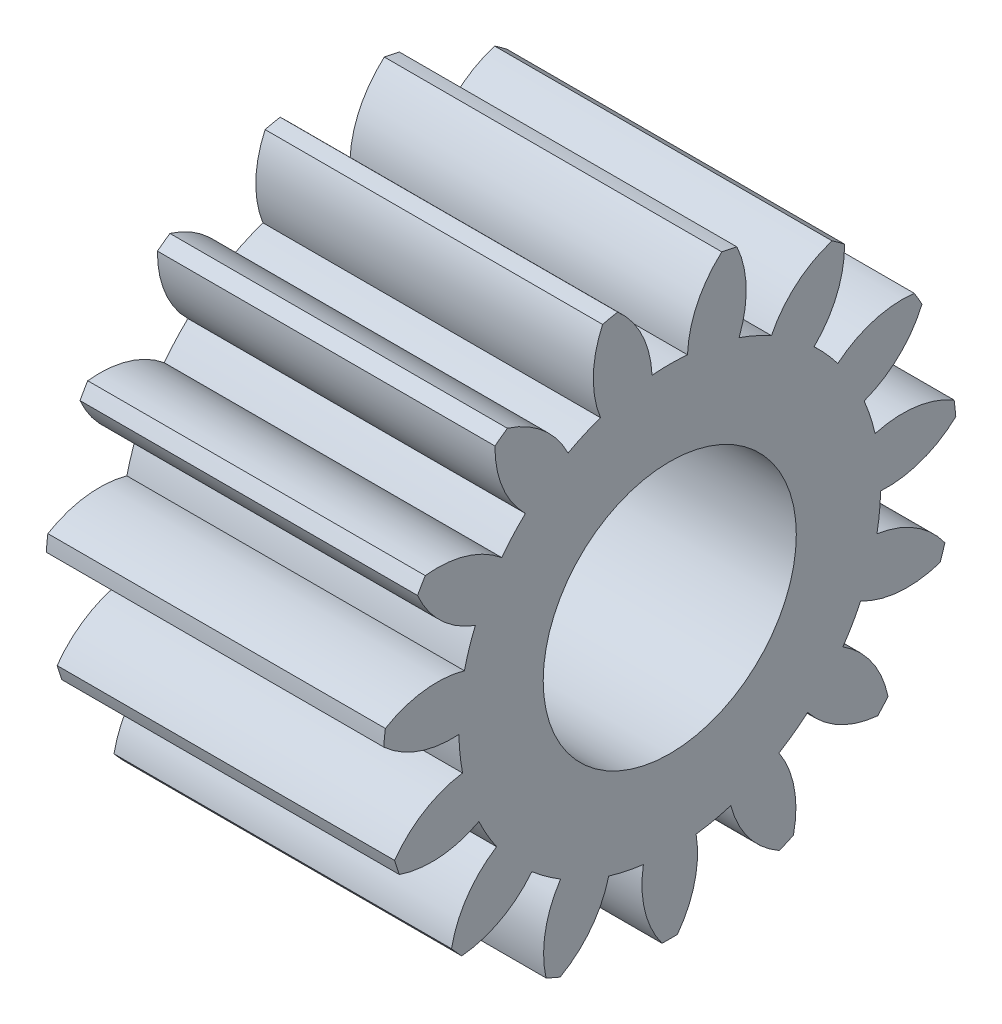
SolidWorks part; units mm, degrees
ref_plane "Plane1" through (0, 0, 0) normal (0, 0, 1) x (1, 0, 0)
ref_plane "Plane2" through (0, 0, 0) normal (0, 1, 0) x (1, 0, 0)
ref_plane "Plane3" through (0, 0, 0) normal (1, 0, 0) x (0, 0, -1)
sketch "HoldingSke" plane through (0, 0, 0) normal (0, 1, 0) x (1, 0, 0)
  line L0 (0, 0) -> (0.483, -0.1294)
  line L1 (-15, 0) -> (100, 0) construction
  line L2 (0, 0) -> (-2.1039, 2.3779)
  line L3 (0, 0) -> (-11.863, 4.5341)
  line L4 (0, 0) -> (8.3417, 2.2352)
  line L5 (0, 0) -> (-46.8476, -17.4728)
  line L6 (0, 0) -> (-16.5793, -11.1861)
  line L7 (-2.1039, 2.3779) -> (8.6586, 51.2059)
  line L8 (-76.2, 54.61) -> (-73.9, 54.61)
  line L9 (-71.009, 38.7566) -> (-53.1078, 45.2721)
  line L10 (-76.2, 71.12) -> (104.1128, 71.12)
  line L11 (0, 0) -> (-20, 0)
  line L12 (-76.2, 101.6) -> (-76.133, 101.6)
  line L13 (24.9733, 27.94) -> (52.9518, 28.4284)
  line L14 (24.9733, 27.94) -> (24.9743, 27.94)
  line L15 (24.9733, 27.94) -> (100.4006, 29.5858)
  line L16 (-63.627, -2) -> (-12.827, -2)
  circle A0 centre (0, 0) radius 7.5
  circle A1 centre (0, 0) radius 12.499
  circle A2 centre (0, 0) radius 37.5
  circle A3 centre (0, 0) radius 7.5
  dimension "MHD" = 24.998
  dimension "Hub_dia" = 75
  dimension "Bore" = 15
  dimension "MBD" = 15
  dimension "Num_teeth" = 15
  dimension "Pitch" = 0.5
  dimension "Overall_len" = 50
  dimension "Show_teeth" = 15
  dimension "Thickness" = 20
  dimension "OAL" = 50.0001
  dimension "T_dim" = 2.3
  dimension "Ap" = 20
  dimension "H" = 19.05
  dimension "Pitch_radius" = 180.3128
  dimension "Width" = 20
  dimension "Backlash" = 0.067
  dimension "Addendum_fac" = 1
  dimension "Dedendum_fac" = 1.25
  dimension "Clearance_fac" = 0.25
  dimension "Dedendum_add" = 0.001
  dimension "Module" = 2
sketch "BasProSke" plane through (0, 0, 0) normal (0, 1, 0) x (1, 0, 0)
  line L0 (-10, 0) -> (60, 0) construction
  line L1 (0, 0) -> (0, 17)
  line L2 (0, 0) -> (20, 0)
  line L3 (20, 0) -> (20, 17)
  line L4 (20, 17) -> (0, 17)
  dimension "Thickness" = 20
  dimension "Diameter" = 34
revolve "Base-Revolve" add sketch "BasProSke" angle 360 about L0
sketch "TooCutSke" plane through (0, 0, 0) normal (1, 0, 0) x (0, 0, -1)
  line L1 (0, 0) -> (0, 107) construction
  line L2 (0, 0) -> (-1.6851, 14.905) construction
  line L3 (0, 0) -> (-6.2081, 29.2069) construction
  line L4 (-1.6851, 14.905) -> (-3.1041, 14.6034) construction
  arc A0 (1.0501, 12.4548) -> (-1.0501, 12.4548) centre (0, 0) ccw
  arc A1 (3.1109, 16.7388) -> (-3.1109, 16.7388) centre (0, 0) ccw
  circle A2 centre (0, 0) radius 15 construction
  circle A3 centre (0, 0) radius 14.0954 construction
  arc A4 (-1.0501, 12.4548) -> (-3.1109, 16.7388) centre (-7.045, 12.2085) ccw
  arc A5 (3.1109, 16.7388) -> (1.0501, 12.4548) centre (7.045, 12.2085) ccw
  dimension "Root_dia" = 24.998
  dimension "Overcut_dia" = 34.0508
  dimension "Pitch_dia" = 30
  dimension "Base_dia" = 28.1908
  dimension "Flank_rad" = 6
  dimension "Half_ang" = 12
  dimension "Half_CT" = 1.4507
extrude "ToothCut" cut sketch "TooCutSke" along normal through all
fillet "Breaks" [suppressed] radius 0.04
fillet "RootFillets" [suppressed] radius 0.501
pattern_circular "TeethCuts" count 15 every 24 about axis through (-10, 0, 0) along (1, 0, 0) of "ToothCut", "RootFillets", "Breaks"
sketch "HubNeaOneSke" plane through (0, 0, 0) normal (-1, 0, 0) x (0, 0, 1)
  circle A0 centre (0, 0) radius 12.499
  dimension "Diameter" = 24.998
extrude "HubNearOne" [suppressed] add sketch "HubNeaOneSke" along normal blind 30.0001
sketch "HubNeaBotSke" plane through (0, 0, 0) normal (-1, 0, 0) x (0, 0, 1)
  circle A0 centre (0, 0) radius 12.499
  dimension "Diameter" = 24.998
extrude "HubNearBoth" [suppressed] add sketch "HubNeaBotSke" along normal blind 15
ref_plane "FarPln" through (20, 0, 0) normal (1, 0, 0) x (0, 0, -1)
sketch "HubFarSke" plane through (20, 0, 0) normal (1, 0, 0) x (0, 0, -1)
  circle A0 centre (0, 0) radius 12.499
  dimension "Diameter" = 24.998
extrude "HubFar" [suppressed] add sketch "HubFarSke" along normal blind 15
sketch "BorSke" plane through (0, 0, 0) normal (1, 0, 0) x (0, 0, -1)
  circle A0 centre (0, 0) radius 7.5
  dimension "Diameter" = 15
extrude "Bore" cut sketch "BorSke" along normal mid plane 100.0001
sketch "KeySke" plane through (0, 0, 0) normal (1, 0, 0) x (0, 0, -1)
  line L0 (-2.5, 0) -> (-2.5, 9.8)
  line L1 (-2.5, 9.8) -> (2.5, 9.8)
  line L2 (2.5, 9.8) -> (2.5, 0)
  line L3 (0, 0) -> (0, 34) construction
  line L4 (-2.5, 0) -> (2.5, 0)
  dimension "Offset" = 9.8
  dimension "Width" = 5
extrude "Keyway" [suppressed] cut sketch "KeySke" along normal mid plane 100.0001
pattern_circular "Keyway2" [suppressed] count 2 every 90 about axis through (-10, 0, 0) along (1, 0, 0)
equation "' \"Module@HoldingSke\" = 6.35"
equation "' \"Num_teeth@HoldingSke\" = 12"
equation "' \"Ap@HoldingSke\" =  20"
equation "' \"Ap@HoldingSke\" = 20"
equation "' \"Width@HoldingSke\" = 0.5 * 25.4"
equation "' \"Hub_dia@HoldingSke\"= 1 * 25.4"
equation "' \"Hub_dia@HoldingSke\" = 1 * 25.4"
equation "' \"Overall_len@HoldingSke\" = 1.0 * 25.4"
equation "' \"Bore@HoldingSke\" = 0.75 * 25.4"
equation "' \"T_dim@HoldingSke\" = 0.1 * 25.4"
equation "' \"Width@KeySke\" = 0.25 * 25.4"
equation "' \"Show_teeth@HoldingSke\" = 13"
equation "' \"Backlash@HoldingSke\" = 0.009 * 25.4"
equation "' \"Addendum_fac@HoldingSke\" = 1.0"
equation "' \"Dedendum_fac@HoldingSke\" = 1.25"
equation "' \"Dedendum_add@HoldingSke\" = 0.00005 * 25.4"
equation "' \"Clearance_fac@HoldingSke\" = 0.25"
equation "\"Pitch@HoldingSke\" = 1 / \"Module@HoldingSke\""
equation "\"Overcut_dia@TooCutSke\" = (\"Num_teeth@HoldingSke\" + 2 * \"Addendum_fac@HoldingSke\") / \"Pitch@HoldingSke\" + 0.002 * 25.4"
equation "\"Pitch_dia@TooCutSke\" = \"Num_teeth@HoldingSke\" / \"Pitch@HoldingSke\""
equation "\"Base_dia@TooCutSke\" = \"Num_teeth@HoldingSke\" / \"Pitch@HoldingSke\" * cos((\"Ap@HoldingSke\"  * 3.14159265 / 180))"
equation "\"Root_dia@TooCutSke\" = (\"Num_teeth@HoldingSke\" + 2) / \"Pitch@HoldingSke\" - 2 * (\"Addendum_fac@HoldingSke\" + \"Dedendum_fac@HoldingSke\") / \"Pitch@HoldingSke\" - \"Dedendum_add@HoldingSke\" * 2"
equation "\"Half_ang@TooCutSke\" = 180 / \"Num_teeth@HoldingSke\""
equation "\"Half_CT@TooCutSke\" = \"Num_teeth@HoldingSke\" / \"Pitch@HoldingSke\" * sin((3.14159265 / 2 / \"Num_teeth@HoldingSke\")) / 2 - 7 * \"Backlash@HoldingSke\" / 4"
equation "\"Flank_rad@TooCutSke\" = \"Num_teeth@HoldingSke\" / \"Pitch@HoldingSke\" / 5"
equation "\"Radius@RootFillets\" = \"Clearance_fac@HoldingSke\" / \"Pitch@HoldingSke\" + \"Dedendum_add@HoldingSke\""
equation "\"Break_rad@Breaks\" = 0.02 / \"Pitch@HoldingSke\""
equation "\"Thickness@HoldingSke\" = \"Width@HoldingSke\""
equation "\"OAL@HoldingSke\" = \"Thickness@HoldingSke\""
equation "\"MHD@HoldingSke\" = (\"Num_teeth@HoldingSke\" + 2) / \"Pitch@HoldingSke\" - 2 * (\"Addendum_fac@HoldingSke\" + \"Dedendum_fac@HoldingSke\")  / \"Pitch@HoldingSke\" - \"Dedendum_add@HoldingSke\" * 2"
equation "\"MBD@HoldingSke\" = (\"Num_teeth@HoldingSke\" + 2) / \"Pitch@HoldingSke\" - 2 * (\"Addendum_fac@HoldingSke\" + \"Dedendum_fac@HoldingSke\")  / \"Pitch@HoldingSke\" - \"Dedendum_add@HoldingSke\" * 2 - 0.002 * 25.4"
equation "\"MHD@HoldingSke\" = ((sgn( \"MHD@HoldingSke\" - \"Hub_dia@HoldingSke\" )-1)*( \"MHD@HoldingSke\" - \"Hub_dia@HoldingSke\" ))/-2+ \"Hub_dia@HoldingSke\""
equation "\"MBD@HoldingSke\" = ((sgn( \"MBD@HoldingSke\" - \"Bore@HoldingSke\" )-1)*( \"MBD@HoldingSke\" - \"Bore@HoldingSke\" ))/-2+ \"Bore@HoldingSke\""
equation "\"OAL@HoldingSke\" = ((sgn( \"OAL@HoldingSke\" - \"Overall_len@HoldingSke\" )+1)*( \"OAL@HoldingSke\" - \"Overall_len@HoldingSke\" ))/2 + \"Overall_len@HoldingSke\" + 0.000002 * 25.4"
equation "\"Num_teeth@TeethCuts\" = int( \"Show_teeth@HoldingSke\" ) + 1"
equation "\"Num_teeth@TeethCuts\" = ((sgn( \"Num_teeth@TeethCuts\" - \"Num_teeth@HoldingSke\" )-1)*( \"Num_teeth@TeethCuts\" - \"Num_teeth@HoldingSke\" ))/-2+ \"Num_teeth@HoldingSke\""
equation "\"Num_teeth@TeethCuts\" = ((sgn( \"Num_teeth@TeethCuts\" - 2.0)+1)*( \"Num_teeth@TeethCuts\" - 2.0))/2 +2.0"
equation "\"Angle@TeethCuts\" = 360.0 / \"Num_teeth@HoldingSke\""
equation "\"Diameter@BasProSke\" = (\"Num_teeth@HoldingSke\" + 2 * \"Addendum_fac@HoldingSke\") / \"Pitch@HoldingSke\""
equation "\"Thickness@BasProSke\"  = \"Thickness@HoldingSke\""
equation "' \"Fillet_rad@BasProSke\" =  \"Thickness@HoldingSke\" * 0.05"
equation "' \"Fillet_rad@BasProSke\" = \"Thickness@HoldingSke\" * 0.05"
equation "\"MHD@HoldingSke\" = ((sgn( \"MHD@HoldingSke\" - \"Root_dia@TooCutSke\" )-1)*( \"MHD@HoldingSke\" - \"Root_dia@TooCutSke\" ))/-2+ \"Root_dia@TooCutSke\""
equation "\"Diameter@HubNeaOneSke\" = \"MHD@HoldingSke\""
equation "\"Length@HubNearOne\" = \"OAL@HoldingSke\" - \"Thickness@BasProSke\""
equation "\"Diameter@HubNeaBotSke\" = \"MHD@HoldingSke\""
equation "\"Length@HubNearBoth\" = ( \"OAL@HoldingSke\" - \"Thickness@BasProSke\" ) / 2.0"
equation "\"Thickness@FarPln\" = \"Thickness@BasProSke\""
equation "\"Diameter@HubFarSke\" = \"MHD@HoldingSke\""
equation "\"Length@HubFar\" = ( \"OAL@HoldingSke\" - \"Thickness@BasProSke\" ) / 2.0"
equation "\"Diameter@BorSke\" = \"MBD@HoldingSke\""
equation "\"D1@Bore\" = \"OAL@HoldingSke\" * 2.0"
equation "\"D1@Keyway\" = \"OAL@HoldingSke\" * 2.0"
equation "\"Offset@KeySke\" = \"T_dim@HoldingSke\" + \"MBD@HoldingSke\" / 2.0"
